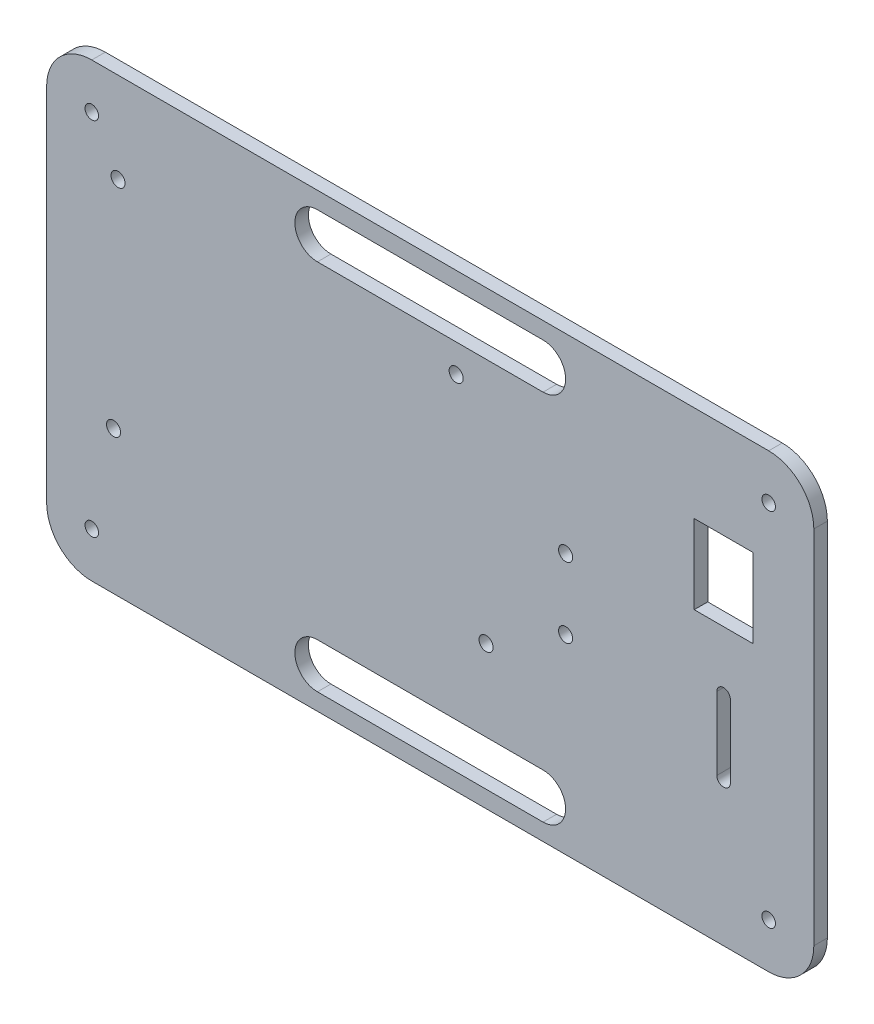
SolidWorks part; units mm, degrees
ref_plane "Front Plane" through (0, 0, 0) normal (0, 0, 1) x (1, 0, 0)
ref_plane "Top Plane" through (0, 0, 0) normal (0, 1, 0) x (1, 0, 0)
ref_plane "Right Plane" through (0, 0, 0) normal (1, 0, 0) x (0, 0, -1)
sketch "Sketch1" plane through (0, 0, 0) normal (0, 0, 1) x (1, 0, 0)
  line L0 (-85, 0) -> (85, 0) construction
  line L1 (-75, 50) -> (75, 50)
  line L2 (-85, 40) -> (-85, -40)
  line L3 (-75, -50) -> (75, -50)
  line L4 (85, 40) -> (85, -40)
  line L5 (-85, 50) -> (85, -50) construction
  line L6 (-85, -50) -> (85, 50) construction
  line L7 (0, 50) -> (0, -50) construction
  line L8 (-25, 41.2578) -> (25, 41.2578) construction
  line L9 (-25, 46.2578) -> (25, 46.2578)
  line L10 (-25, 36.2578) -> (25, 36.2578)
  line L11 (-25, -41.2578) -> (25, -41.2578) construction
  line L12 (-25, -46.2578) -> (25, -46.2578)
  line L13 (-25, -36.2578) -> (25, -36.2578)
  line L39 (65, -1.95) -> (65, -18.05) construction
  line L40 (58.5, 28.75) -> (71.5, 28.75)
  line L41 (58.5, 28.75) -> (58.5, 11.25)
  line L42 (58.5, 11.25) -> (71.5, 11.25)
  line L43 (71.5, 28.75) -> (71.5, 11.25)
  line L44 (58.5, 28.75) -> (71.5, 11.25) construction
  line L45 (58.5, 11.25) -> (71.5, 28.75) construction
  line L46 (66.5, -1.95) -> (66.5, -18.05)
  line L47 (63.5, -1.95) -> (63.5, -18.05)
  arc A0 (-25, 46.2578) -> (-25, 36.2578) centre (-25, 41.2578) ccw
  arc A1 (25, 36.2578) -> (25, 46.2578) centre (25, 41.2578) ccw
  arc A2 (-25, -46.2578) -> (-25, -36.2578) centre (-25, -41.2578) cw
  arc A3 (25, -36.2578) -> (25, -46.2578) centre (25, -41.2578) cw
  arc A18 (66.5, -1.95) -> (63.5, -1.95) centre (65, -1.95) ccw
  arc A19 (63.5, -18.05) -> (66.5, -18.05) centre (65, -18.05) ccw
  arc A20 (75, 50) -> (85, 40) centre (75, 40) cw
  arc A21 (85, -40) -> (75, -50) centre (75, -40) cw
  arc A22 (-75, -50) -> (-85, -40) centre (-75, -40) cw
  arc A23 (-75, 50) -> (-85, 40) centre (-75, 40) ccw
  circle A24 centre (-75, 40) radius 1.5
  circle A25 centre (-75, -40) radius 1.5
  circle A26 centre (75, -40) radius 1.5
  circle A27 centre (75, 40) radius 1.5
  circle A30 centre (-69.18, 30) radius 1.56
  circle A31 centre (5.75, 30) radius 1.56
  circle A32 centre (12.37, -18.3) radius 1.56
  circle A33 centre (-70.18, -18.3) radius 1.56
  circle A34 centre (30, 7.78) radius 1.56
  circle A35 centre (30, -7.78) radius 1.56
  point P0 (0, 0)
  point P12 (0, 41.2578)
  point P19 (0, -41.2578)
  point P73 (65, 20)
  point P80 (65, -10)
  dimension "D3" = 5
  dimension "D11" = 74.93
  dimension "D14" = 15.82
  dimension "D17" = 3.12
  dimension "D18" = 30
  dimension "D16" = 15.56
  dimension "D28" = 16.1
  dimension "D31" = 10
  dimension "D32" = 3
  dimension "D6" = 3.12
  dimension "D7" = 3.12
  dimension "D8" = 3.12
  dimension "D9" = 3.12
  dimension "D1" = 170
  dimension "D2" = 100
  dimension "D4" = 50
  dimension "D5" = 41.2578
  dimension "D10" = 82.55
  dimension "D12" = 48.3
  dimension "D13" = 20
  dimension "D15" = 14.82
  dimension "D19" = 7.78
  dimension "D24" = 13
  dimension "D25" = 17.5
  dimension "D26" = 20
  dimension "D27" = 20
  dimension "D29" = 3
  dimension "D30" = 10
  dimension "D33" = 80
  dimension "D34" = 40
  dimension "D35" = 150
  dimension "D36" = 150
  dimension "D37" = 75
extrude "Boss-Extrude1" add sketch "Sketch1" along normal blind 3
